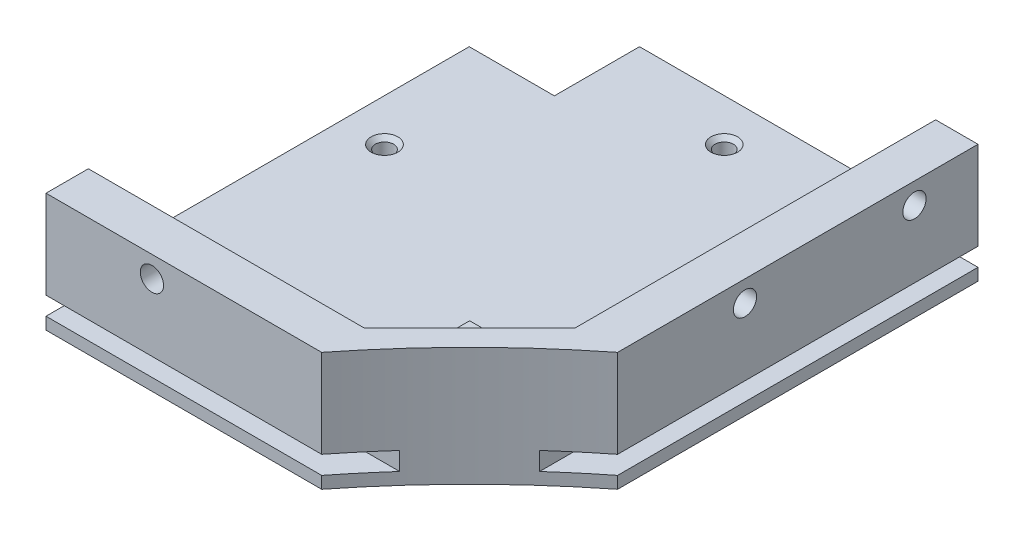
SolidWorks part; units mm, degrees
ref_plane "Front Plane" through (0, 0, 0) normal (0, 0, 1) x (1, 0, 0)
ref_plane "Top Plane" through (0, 0, 0) normal (0, 1, 0) x (1, 0, 0)
ref_plane "Right Plane" through (0, 0, 0) normal (1, 0, 0) x (0, 0, -1)
sketch "Sketch1" plane through (0, 0, 0) normal (0, 1, 0) x (1, 0, 0)
  line L0 (0, 0) -> (0, 650)
  line L1 (0, 650) -> (650, 650)
  line L2 (650, 650) -> (650, 0)
  line L3 (650, 0) -> (0, 0)
  dimension "D1" = 650
  dimension "D2" = 650
extrude "Boss-Extrude1" add sketch "Sketch1" along normal blind 8
sketch "Sketch3" plane through (0, 0, 0) normal (0, 0, 1) x (1, 0, 0)
  line L0 (325, 8) -> (325, 43.7071) construction
  line L1 (0, 8) -> (650, 8) construction
  line L2 (300, 43.7071) -> (350, 43.7071)
  line L3 (300, 43.7071) -> (265, 8)
  line L4 (265, 8) -> (385, 8)
  line L5 (385, 8) -> (350, 43.7071)
  point P7 (325, 43.7071)
  dimension "D1" = 50
  dimension "D2" = 50
  dimension "D3" = 50
  dimension "D4" = 120
extrude "Boss-Extrude2" add sketch "Sketch3" against normal blind 650
sketch "Sketch4" plane through (0, 0, 0) normal (0, 0, 1) x (1, 0, 0)
  line L0 (265, 8) -> (385, 8) construction
  circle A0 centre (325, 22) radius 11
  dimension "D1" = 14
extrude "Cut-Extrude2" cut sketch "Sketch4" against normal through all both and the other way through all
sketch "Sketch2" plane through (0, 8, 0) normal (0, 1, 0) x (1, 0, 0)
  line L0 (0, 650) -> (0, 0) construction
  line L1 (650, 650) -> (385, 650) construction
  circle A0 centre (325, 325) radius 210
  dimension "D3" = 420
  dimension "D1" = 325
  dimension "D2" = 325
extrude "Cut-Extrude1" cut sketch "Sketch2" against normal through all both and the other way through all
sketch "Sketch5" plane through (0, 0, 0) normal (0, 0, 1) x (1, 0, 0)
  line L0 (300, 43.7071) -> (350, 43.7071)
  line L1 (265, 8) -> (385, 8) construction
  line L2 (300, 8) -> (300, 28)
  line L3 (300, 8) -> (350, 8)
  line L4 (350, 8) -> (350, 28)
  line L5 (350, 28) -> (365.3961, 28)
  line L6 (385, 8) -> (350, 43.7071) construction
  line L7 (365.3961, 28) -> (350, 43.7071)
  line L8 (300, 28) -> (284.6039, 28)
  line L9 (300, 43.7071) -> (265, 8) construction
  line L10 (284.6039, 28) -> (300, 43.7071)
extrude "Cut-Extrude3" cut sketch "Sketch5" against normal blind 110 and the other way through all
sketch "Sketch6" plane through (0, 0, -650) normal (0, 0, -1) x (-1, 0, 0)
  line L0 (-265, 8) -> (-385, 8) construction
  line L1 (-350, 43.7071) -> (-300, 43.7071)
  line L2 (-300, 8) -> (-300, 28)
  line L3 (-300, 28) -> (-284.6039, 28)
  line L4 (-300, 43.7071) -> (-265, 8) construction
  line L5 (-284.6039, 28) -> (-300, 43.7071)
  line L6 (-350, 8) -> (-350, 28)
  line L7 (-350, 28) -> (-365.3961, 28)
  line L8 (-365.3961, 28) -> (-350, 43.7071)
  line L9 (-350, 8) -> (-300, 8)
extrude "Cut-Extrude4" cut sketch "Sketch6" against normal blind 110
sketch "Sketch7" plane through (0, 8, 0) normal (0, 1, 0) x (1, 0, 0)
  line L1 (325, 325) -> (325, 455) construction
  line L2 (325, 325) -> (325, 195) construction
  line L3 (325, 325) -> (455, 325) construction
  line L4 (325, 325) -> (195, 325) construction
  line L9 (325, 455) -> (455, 455) construction
  line L10 (455, 455) -> (455, 195) construction
  line L11 (455, 195) -> (195, 195) construction
  line L12 (195, 195) -> (195, 455) construction
  line L13 (195, 455) -> (325, 455) construction
  line L14 (195, 455) -> (195, 489.9242)
  line L15 (195, 489.9242) -> (195, 650)
  line L16 (265, 650) -> (0, 650) construction
  line L17 (195, 455) -> (160.0758, 455)
  line L18 (160.0758, 455) -> (0, 455)
  line L19 (0, 650) -> (0, 0) construction
  line L20 (0, 455) -> (-70.8389, 472.4621)
  line L21 (-70.8389, 472.4621) -> (-70.8389, 686.5445)
  line L22 (-70.8389, 686.5445) -> (167.4782, 686.5445)
  line L23 (167.4782, 686.5445) -> (195, 650)
  arc A0 (265, 526.2461) -> (265, 123.7539) centre (325, 325) ccw construction
  dimension "D1" = 130
  dimension "D2" = 130
  dimension "D3" = 130
  dimension "D4" = 130
extrude "Cut-Extrude5" cut sketch "Sketch7" against normal through all both and the other way through all flip side to cut
sketch "Sketch8" plane through (0, 0, -650) normal (0, 0, -1) x (-1, 0, 0)
  line L0 (-195, 8) -> (-195, 28)
  line L1 (-195, 28) -> (-185, 28)
  line L2 (-185, 28) -> (-185, 17)
  line L3 (-185, 17) -> (-175, 8)
  line L4 (-195, 8) -> (0, 8) construction
  line L5 (-175, 8) -> (-195, 8)
  dimension "D1" = 10
  dimension "D2" = 20
  dimension "D3" = 11
  dimension "D4" = 20
extrude "Boss-Extrude3" add sketch "Sketch8" against normal blind 160.08
sketch "Sketch10" plane through (0, 0, 0) normal (-1, 0, 0) x (0, 0, 1)
  line L0 (-455, 8) -> (-455, 28)
  line L1 (-455, 28) -> (-465, 28)
  line L2 (-465, 28) -> (-465, 17)
  line L3 (-465, 17) -> (-475, 8)
  line L4 (-650, 8) -> (-455, 8) construction
  line L5 (-475, 8) -> (-455, 8)
  dimension "D1" = 10
  dimension "D2" = 20
  dimension "D3" = 11
  dimension "D4" = 20
extrude "Boss-Extrude4" add sketch "Sketch10" against normal blind 160.08
sketch "Sketch21" plane through (0, 0, 0) normal (-1, 0, 0) x (0, 0, 1)
  line L0 (-455, 7.15) -> (-465, 7.15)
  line L1 (-455, 0) -> (-455, 28) construction
  line L2 (-465, 7.15) -> (-465, 2.85)
  line L3 (-465, 2.85) -> (-455, 2.85)
  line L4 (-455, 2.85) -> (-455, 7.15)
  line L5 (-650, 0) -> (-455, 0) construction
  dimension "D1" = 2.85
  dimension "D2" = 4.3
extrude "Cut-Extrude10" cut sketch "Sketch21" against normal through all
sketch "Sketch22" plane through (0, 0, -650) normal (0, 0, -1) x (-1, 0, 0)
  line L0 (-195, 7.15) -> (-185, 7.15)
  line L1 (-195, 0) -> (-195, 28) construction
  line L2 (-185, 7.15) -> (-185, 2.85)
  line L3 (-185, 2.85) -> (-195, 2.85)
  line L4 (-195, 2.85) -> (-195, 7.15)
  line L5 (-195, 0) -> (0, 0) construction
  dimension "D1" = 2.85
  dimension "D2" = 4.3
extrude "Cut-Extrude11" cut sketch "Sketch22" against normal through all
sketch "Sketch12" plane through (0, 8, 0) normal (0, 1, 0) x (1, 0, 0)
  line L0 (0, 0) -> (0, 650) construction
  line L1 (0, 650) -> (650, 650) construction
  line L2 (650, 650) -> (0, 0) construction
  circle A0 centre (325, 325) radius 210
sketch "Sketch23" plane through (0, 0, -489.92) normal (0, 0, 1) x (1, 0, 0)
  line L3 (194.9946, 8) -> (195, 28)
  line L4 (195, 28) -> (160.08, 28)
  line L5 (160.08, 28) -> (160.08, 8)
  line L6 (160.08, 8) -> (194.9946, 8)
extrude "Boss-Extrude5" add sketch "Sketch23" along normal blind 60
extrude "Cut-Extrude6" cut sketch "Sketch12" against normal through all both and the other way through all
sketch "Sketch26" plane through (0, 28, 0) normal (0, 1, 0) x (1, 0, 0)
  line L0 (185, 489.92) -> (160.08, 489.92)
  line L1 (160.08, 489.92) -> (160.08, 465)
  line L2 (160.08, 465) -> (185, 489.92)
extrude "Cut-Extrude14" cut sketch "Sketch26" against normal blind 11
sketch "Sketch27" plane through (185, 0, 0) normal (-1, 0, 0) x (0, 0, 1)
  line L0 (-650, 17) -> (-650, 28) construction
  line L1 (-489.92, 28) -> (-650, 28) construction
  circle A0 centre (-610, 23) radius 2.2
  circle A1 centre (-560, 23) radius 2.75
  circle A2 centre (-520, 23) radius 2.75
  dimension "D1" = 40
  dimension "D7" = 5.5
  dimension "D8" = 5.5
  dimension "D2" = 50
  dimension "D3" = 40
  dimension "D4" = 5
  dimension "D5" = 5
  dimension "D6" = 5
extrude "Cut-Extrude15" cut sketch "Sketch27" against normal blind 11
sketch "Sketch28" plane through (0, 0, -465) normal (0, 0, -1) x (-1, 0, 0)
  line L0 (0, 28) -> (0, 17) construction
  line L1 (-160.08, 28) -> (0, 28) construction
  circle A0 centre (-120, 23) radius 2.75
  circle A1 centre (-80, 23) radius 2.2
  circle A2 centre (-40, 23) radius 2.2
  dimension "D1" = 5.5
  dimension "D2" = 4.4
  dimension "D3" = 4.4
  dimension "D4" = 40
  dimension "D5" = 40
  dimension "D6" = 40
  dimension "D7" = 5
  dimension "D8" = 5
  dimension "D9" = 5
extrude "Cut-Extrude16" cut sketch "Sketch28" against normal blind 11
sketch "Sketch29" plane through (0, 8, 0) normal (0, 1, 0) x (1, 0, 0)
  line L0 (0, 650) -> (20, 650)
  line L1 (175, 650) -> (0, 650) construction
  line L2 (20, 650) -> (20, 630)
  line L3 (20, 630) -> (0, 630)
  line L4 (0, 650) -> (0, 475) construction
  line L5 (0, 630) -> (0, 650)
extrude "Cut-Extrude17" cut sketch "Sketch29" against normal blind 10
sketch "Sketch30" plane through (0, 8, 0) normal (0, 1, 0) x (1, 0, 0)
  line L6 (95, 650) -> (0, 650)
  line L7 (175, 650) -> (20, 650) construction
  line L8 (0, 650) -> (0, 455)
  line L9 (0, 630) -> (0, 475) construction
  line L10 (0, 455) -> (95, 455)
  line L11 (95, 650) -> (95, 455)
  dimension "D1" = 195
  dimension "D2" = 95
  dimension "D3" = 95
extrude "Cut-Extrude18" cut sketch "Sketch30" against normal through all both and the other way through all
sketch "Sketch31" plane through (0, 8, 0) normal (0, 1, 0) x (1, 0, 0)
  line L0 (95, 650) -> (95, 575)
  line L1 (95, 650) -> (95, 475) construction
  line L2 (95, 650) -> (195, 650)
  line L3 (195, 650) -> (195, 575)
  line L4 (195, 489.9242) -> (195, 650) construction
  line L5 (195, 575) -> (95, 575)
extrude "Cut-Extrude19" cut sketch "Sketch31" against normal through all both and the other way through all
sketch "Sketch32" plane through (0, 8, 0) normal (0, 1, 0) x (1, 0, 0)
  line L0 (95, 575) -> (115.1, 575)
  line L1 (175, 575) -> (95, 575) construction
  line L2 (115.1, 575) -> (115.1, 554.9)
  line L3 (115.1, 554.9) -> (95, 554.9)
  line L4 (95, 575) -> (95, 475) construction
  line L5 (95, 554.9) -> (95, 575)
  dimension "D1" = 20.1
  dimension "D2" = 20.1
extrude "Cut-Extrude20" cut sketch "Sketch32" against normal blind 10
sketch "Sketch33" plane through (0, 8, 0) normal (0, 1, 0) x (1, 0, 0)
  line L0 (175, 575) -> (115.1, 575) construction
  line L1 (95, 554.9) -> (95, 475) construction
  line L2 (115.1, 554.9) -> (115.1, 575) construction
  line L3 (95, 554.9) -> (115.1, 554.9) construction
  circle A0 centre (105, 524.9) radius 2.15
  circle A1 centre (145.1, 565) radius 2.15
  dimension "D1" = 4.3
  dimension "D2" = 4.3
  dimension "D3" = 10
  dimension "D4" = 10
  dimension "D5" = 30
  dimension "D6" = 30
extrude "Cut-Extrude21" cut sketch "Sketch33" against normal blind 10
chamfer "Chamfer1" distance 1 angle 45 2 edges at (105, 8, -522.75) (145.1, 8, -562.85)
